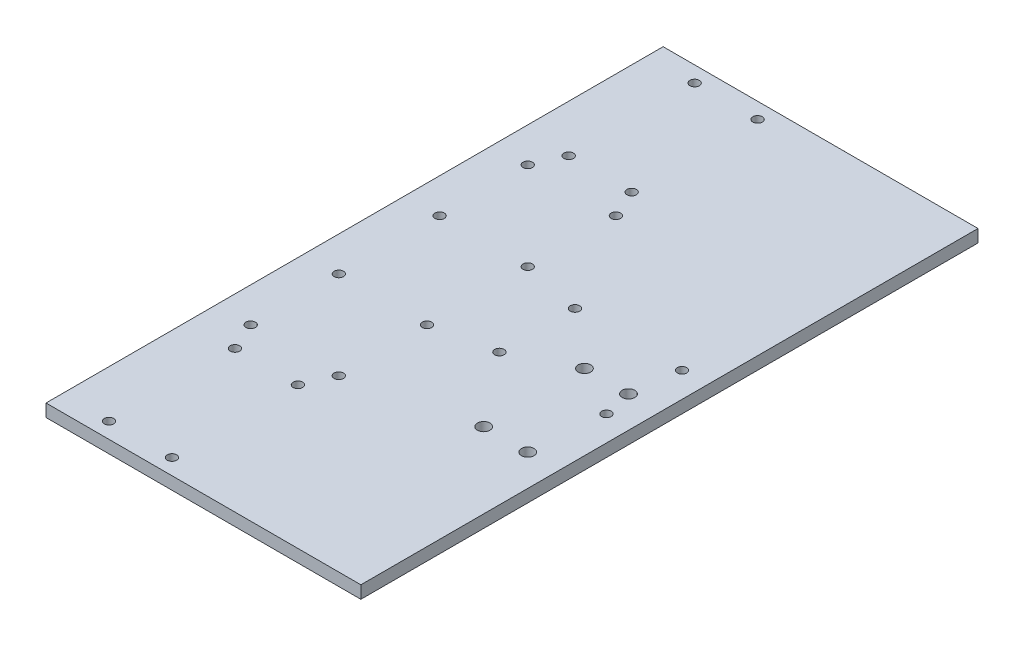
SolidWorks part; units mm, degrees
ref_plane "前视基准面" through (0, 0, 0) normal (0, 0, 1) x (1, 0, 0)
ref_plane "上视基准面" through (0, 0, 0) normal (0, 1, 0) x (1, 0, 0)
ref_plane "右视基准面" through (0, 0, 0) normal (1, 0, 0) x (0, 0, -1)
other "Configuration Table"
sketch "草图1" plane through (0, 0, 0) normal (0, 1, 0) x (1, 0, 0)
  line L0 (-50, -80) -> (50, -80)
  line L1 (-50, -80) -> (-50, 80)
  line L2 (-50, 80) -> (50, 80)
  line L3 (50, -80) -> (50, 80)
  line L4 (-50, -80) -> (50, 80) construction
  line L5 (-50, 80) -> (50, -80) construction
  point P0 (0, 0)
  dimension "D1" = 160
  dimension "D2" = 100
extrude "凸台-拉伸1" add sketch "草图1" along normal blind 4
sketch "草图2" plane through (0, 4, 0) normal (0, 1, 0) x (1, 0, 0)
  line L0 (-50, -80) -> (50, -80) construction
  line L1 (50, -80) -> (50, 80) construction
  circle A0 centre (40, -3) radius 2
  circle A1 centre (26, -3) radius 2
  circle A2 centre (40, -35) radius 2
  circle A3 centre (26, -35) radius 2
  dimension "D1" = 4
  dimension "D2" = 4
  dimension "D3" = 14
  dimension "D4" = 32
  dimension "D5" = 45
  dimension "D6" = 10
extrude "切除-拉伸1" cut sketch "草图2" against normal blind 4
sketch "草图3" plane through (0, 4, 0) normal (0, 1, 0) x (1, 0, 0)
  line L1 (-39, 44) -> (-11, 44) construction
  line L2 (-39, 44) -> (-39, 16) construction
  line L3 (-39, 16) -> (-11, 16) construction
  line L4 (-11, 44) -> (-11, 16) construction
  line L5 (-39, 44) -> (-11, 16) construction
  line L6 (-39, 16) -> (-11, 44) construction
  circle A0 centre (-39, 44) radius 1.5
  circle A1 centre (-11, 44) radius 1.5
  circle A2 centre (-11, 16) radius 1.5
  circle A3 centre (-39, 16) radius 1.5
  point P0 (-25, 30)
  dimension "D3" = 3
  dimension "D1" = 28
  dimension "D2" = 25
  dimension "D4" = 16
extrude "切除-拉伸2" cut sketch "草图3" against normal blind 4
mirror "镜向1" about plane through (0, 0, 0) normal (0, 0, 1) of "切除-拉伸2"
sketch "草图4" plane through (0, 4, 0) normal (0, 1, 0) x (1, 0, 0)
  line L0 (25, 80) -> (25, -80) construction
  line L1 (-50, 0) -> (50, 0) construction
  line L2 (-50, 80) -> (-50, -80) construction
  line L3 (50, -80) -> (50, 80) construction
  line L4 (50, 80) -> (-50, 80) construction
  line L5 (-50, -80) -> (50, -80) construction
  circle A0 centre (42, 12) radius 1.5
  circle A1 centre (8, 12) radius 1.5
  circle A2 centre (42, -12) radius 1.5
  circle A3 centre (8, -12) radius 1.5
  dimension "D1" = 3
  dimension "D2" = 24
  dimension "D3" = 34
  dimension "D4" = 25
extrude "切除-拉伸3" cut sketch "草图4" against normal blind 4
sketch "草图6" plane through (0, 0, -80) normal (0, 0, -1) x (-1, 0, 0)
  line L4 (-50, 0) -> (50, 0)
  line L5 (50, 0) -> (50, 4)
  line L6 (50, 4) -> (-50, 4)
  line L7 (-50, 4) -> (-50, 0)
  line L8 (-50, 0) -> (50, 0)
  line L9 (50, 0) -> (50, 4)
  line L10 (50, 4) -> (-50, 4)
  line L11 (-50, 4) -> (-50, 0)
  dimension "D1" = 0
extrude "凸台-拉伸2" add sketch "草图6" along normal blind 18
sketch "草图5" plane through (0, 4, 0) normal (0, 1, 0) x (1, 0, 0)
  line L1 (-50, 98) -> (-50, -80) construction
  line L2 (-50, 98) -> (50, 98) construction
  circle A0 centre (-35, 93) radius 1.5
  dimension "D1" = 3
  dimension "D2" = 5
  dimension "D3" = 15
extrude "切除-拉伸4" cut sketch "草图5" against normal blind 10
mirror "镜向2" about plane through (0, 0, 0) normal (0, 0, 1) of "凸台-拉伸2"
pattern_linear "阵列(线性)1" count 2 spacing 40 along (0, 0, 1) count 2 spacing 20 along (1, 0, 0) of "切除-拉伸4"
mirror "镜向3" about plane through (0, 0, 0) normal (0, 0, 1) of "阵列(线性)1", "切除-拉伸4"
